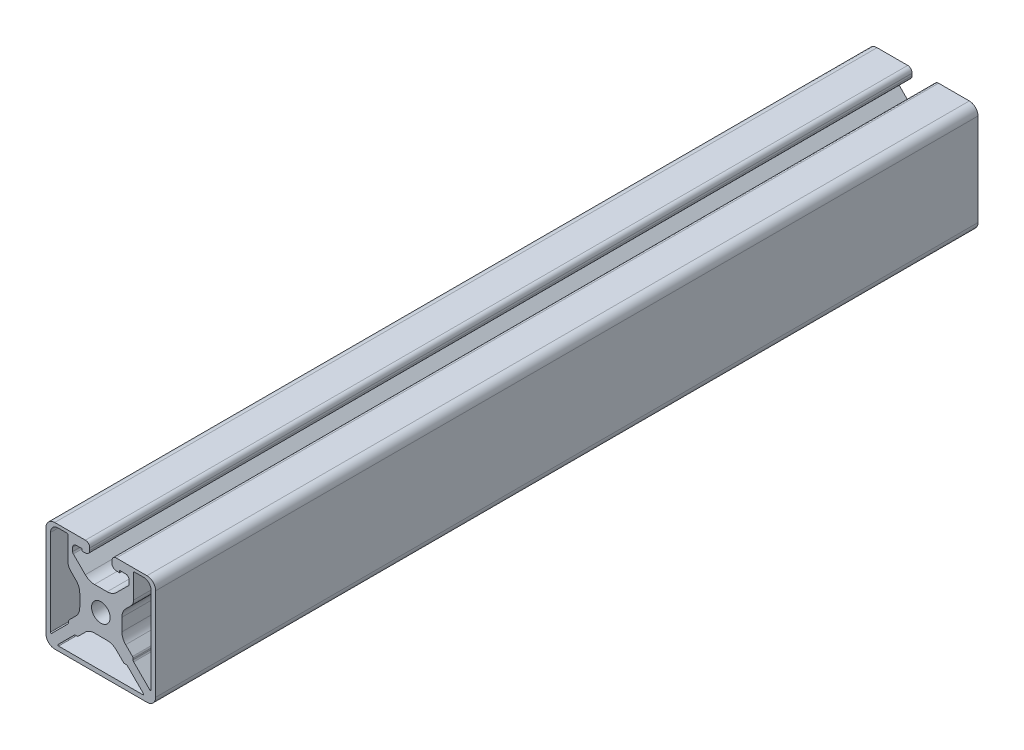
SolidWorks part; units mm, degrees
material "6105-T5 Aluminum"
ref_plane "Front Plane" through (0, 0, 0) normal (0, 0, 1) x (1, 0, 0)
ref_plane "Top Plane" through (0, 0, 0) normal (0, 1, 0) x (1, 0, 0)
ref_plane "Right Plane" through (0, 0, 0) normal (1, 0, 0) x (0, 0, -1)
sketch "Sketch1" plane through (0, 0, 0) normal (0, 0, 1) x (1, 0, 0)
  line L0 (-7.685, -2.3065) -> (-7.685, 2.3065)
  line L1 (-11.5462, -8.1351) -> (-9.0762, -5.6651)
  line L2 (-11.7694, -9.1203) -> (-11.7694, -8.6739)
  line L3 (-17.8962, -15.5627) -> (-11.9926, -9.6591)
  line L4 (-18.35, 16.0956) -> (-18.35, -15.3747)
  line L5 (-12.3431, 18.8896) -> (-15.556, 18.8896)
  line L6 (-11.9621, 9.8662) -> (-11.9621, 18.5086)
  line L7 (-9.0762, 5.6651) -> (-11.0322, 7.6211)
  line L8 (11.7694, -8.6739) -> (11.7694, -9.1203)
  line L9 (9.0762, -5.6651) -> (11.5462, -8.1351)
  line L10 (7.685, 2.3065) -> (7.685, -2.3065)
  line L11 (11.0322, 7.6211) -> (9.0762, 5.6651)
  line L12 (11.9621, 18.5086) -> (11.9621, 9.8662)
  line L13 (15.556, 18.8896) -> (12.3431, 18.8896)
  line L14 (18.35, -15.3747) -> (18.35, 16.0956)
  line L15 (11.9926, -9.6591) -> (17.8962, -15.5627)
  line L16 (15.5882, -17.9217) -> (9.7291, -12.0626)
  line L17 (-15.4108, -18.35) -> (15.4108, -18.35)
  line L18 (-9.7291, -12.0626) -> (-15.5882, -17.9217)
  line L19 (-8.7439, -11.8394) -> (-9.1903, -11.8394)
  line L20 (-5.6651, -9.0762) -> (-8.2051, -11.6162)
  line L21 (2.3065, -7.685) -> (-2.3065, -7.685)
  line L22 (8.2051, -11.6162) -> (5.6651, -9.0762)
  line L23 (9.1903, -11.8394) -> (8.7439, -11.8394)
  line L24 (16.825, 20) -> (5.6287, 20)
  line L25 (4.06, 18.2867) -> (4.06, 17.5148)
  line L26 (5.6348, 15.94) -> (6.8724, 15.94)
  line L27 (6.8724, 15.94) -> (6.899, 16.702)
  line L28 (6.899, 16.702) -> (9.015, 16.702)
  line L29 (10.285, 15.432) -> (10.285, 14.0643)
  line L30 (10.0246, 13.4357) -> (5.6651, 9.0762)
  line L31 (2.3065, 7.685) -> (-2.3065, 7.685)
  line L32 (-5.6651, 9.0762) -> (-10.0246, 13.4357)
  line L33 (-10.285, 14.0643) -> (-10.285, 15.432)
  line L34 (-9.015, 16.702) -> (-6.899, 16.702)
  line L35 (-6.899, 16.702) -> (-6.8724, 15.94)
  line L36 (-6.8724, 15.94) -> (-5.6348, 15.94)
  line L37 (-4.06, 17.5148) -> (-4.06, 18.2867)
  line L38 (-5.6287, 20) -> (-16.825, 20)
  line L39 (-20, 16.825) -> (-20, -16.825)
  line L40 (-16.825, -20) -> (16.825, -20)
  line L41 (20, -16.825) -> (20, 16.825)
  arc A0 (-9.0762, -5.6651) -> (-7.685, -2.3065) centre (-12.4348, -2.3065) ccw
  arc A1 (-11.5462, -8.1351) -> (-11.7694, -8.6739) centre (-11.0074, -8.6739) ccw
  arc A2 (-11.9926, -9.6591) -> (-11.7694, -9.1203) centre (-12.5314, -9.1203) ccw
  arc A3 (-18.35, -15.3747) -> (-17.8962, -15.5627) centre (-18.0841, -15.3747) ccw
  arc A4 (-15.556, 18.8896) -> (-18.35, 16.0956) centre (-15.556, 16.0956) ccw
  arc A5 (-11.9621, 18.5086) -> (-12.3431, 18.8896) centre (-12.3431, 18.5086) ccw
  arc A6 (-11.9621, 9.8662) -> (-11.0322, 7.6211) centre (-8.7871, 9.8662) ccw
  arc A7 (-7.685, 2.3065) -> (-9.0762, 5.6651) centre (-12.4348, 2.3065) ccw
  arc A8 (11.7694, -8.6739) -> (11.5462, -8.1351) centre (11.0074, -8.6739) ccw
  arc A9 (7.685, -2.3065) -> (9.0762, -5.6651) centre (12.4348, -2.3065) ccw
  arc A10 (9.0762, 5.6651) -> (7.685, 2.3065) centre (12.4348, 2.3065) ccw
  arc A11 (11.0322, 7.6211) -> (11.9621, 9.8662) centre (8.7871, 9.8662) ccw
  arc A12 (12.3431, 18.8896) -> (11.9621, 18.5086) centre (12.3431, 18.5086) ccw
  arc A13 (18.35, 16.0956) -> (15.556, 18.8896) centre (15.556, 16.0956) ccw
  arc A14 (17.8962, -15.5627) -> (18.35, -15.3747) centre (18.0841, -15.3747) ccw
  arc A15 (11.7694, -9.1203) -> (11.9926, -9.6591) centre (12.5314, -9.1203) ccw
  arc A16 (15.4108, -18.35) -> (15.5882, -17.9217) centre (15.4108, -18.0991) ccw
  arc A17 (-15.5882, -17.9217) -> (-15.4108, -18.35) centre (-15.4108, -18.0991) ccw
  arc A18 (-9.1903, -11.8394) -> (-9.7291, -12.0626) centre (-9.1903, -12.6014) ccw
  arc A19 (-8.7439, -11.8394) -> (-8.2051, -11.6162) centre (-8.7439, -11.0774) ccw
  arc A20 (-2.3065, -7.685) -> (-5.6651, -9.0762) centre (-2.3065, -12.4348) ccw
  arc A21 (5.6651, -9.0762) -> (2.3065, -7.685) centre (2.3065, -12.4348) ccw
  arc A22 (8.2051, -11.6162) -> (8.7439, -11.8394) centre (8.7439, -11.0774) ccw
  arc A23 (9.7291, -12.0626) -> (9.1903, -11.8394) centre (9.1903, -12.6014) ccw
  circle A24 centre (0, 0) radius 3.4
  arc A25 (20, 16.825) -> (16.825, 20) centre (16.825, 16.825) ccw
  arc A26 (5.6287, 20) -> (4.06, 18.2867) centre (5.6287, 18.4252) ccw
  arc A27 (4.06, 17.5148) -> (5.6348, 15.94) centre (5.6348, 17.5148) ccw
  arc A28 (10.285, 15.432) -> (9.015, 16.702) centre (9.015, 15.432) ccw
  arc A29 (10.0246, 13.4357) -> (10.285, 14.0643) centre (9.396, 14.0643) ccw
  arc A30 (2.3065, 7.685) -> (5.6651, 9.0762) centre (2.3065, 12.4348) ccw
  arc A31 (-5.6651, 9.0762) -> (-2.3065, 7.685) centre (-2.3065, 12.4348) ccw
  arc A32 (-10.285, 14.0643) -> (-10.0246, 13.4357) centre (-9.396, 14.0643) ccw
  arc A33 (-9.015, 16.702) -> (-10.285, 15.432) centre (-9.015, 15.432) ccw
  arc A34 (-5.6348, 15.94) -> (-4.06, 17.5148) centre (-5.6348, 17.5148) ccw
  arc A35 (-4.06, 18.2867) -> (-5.6287, 20) centre (-5.6287, 18.4252) ccw
  arc A36 (-16.825, 20) -> (-20, 16.825) centre (-16.825, 16.825) ccw
  arc A37 (-20, -16.825) -> (-16.825, -20) centre (-16.825, -16.825) ccw
  arc A38 (16.825, -20) -> (20, -16.825) centre (16.825, -16.825) ccw
extrude "Extrude1" add sketch "Sketch1" against normal blind 300
